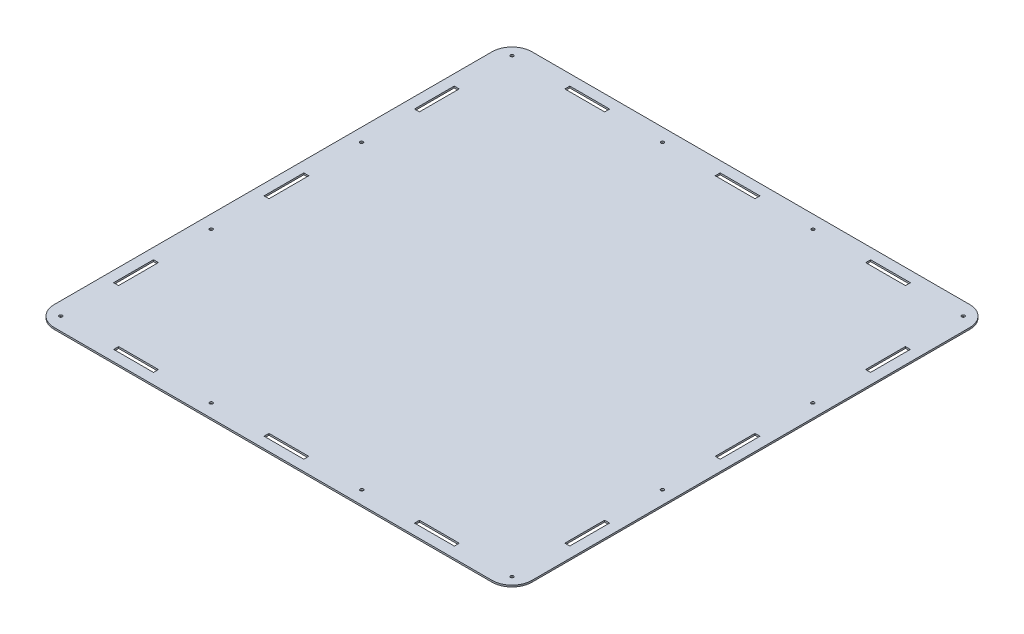
SolidWorks part; units mm, degrees
ref_plane "Front Plane" through (0, 0, 0) normal (0, 0, 1) x (1, 0, 0)
ref_plane "Top Plane" through (0, 0, 0) normal (0, 1, 0) x (1, 0, 0)
ref_plane "Right Plane" through (0, 0, 0) normal (1, 0, 0) x (0, 0, -1)
sketch "Sketch1" plane through (0, 0, 0) normal (0, 1, 0) x (1, 0, 0)
  line L1 (228.6, -228.6) -> (-228.6, -228.6)
  line L2 (228.6, -228.6) -> (228.6, 228.6)
  line L3 (228.6, 228.6) -> (-228.6, 228.6)
  line L4 (-228.6, -228.6) -> (-228.6, 228.6)
  line L5 (228.6, -228.6) -> (-228.6, 228.6) construction
  line L6 (228.6, 228.6) -> (-228.6, -228.6) construction
  point P0 (0, 0)
  dimension "D1" = 457.2
extrude "Boss-Extrude1" add sketch "Sketch1" along normal blind 1.5875
sketch "Sketch2" plane through (0, 1.5875, 0) normal (0, 1, 0) x (1, 0, 0)
  line L0 (-213.5187, -124.8833) -> (-218.2812, -124.8833) construction
  line L1 (-218.2812, -124.8833) -> (-218.2812, -162.9833) construction
  line L2 (-218.2812, -162.9833) -> (-213.5187, -162.9833) construction
  line L3 (-213.5187, -162.9833) -> (-213.5187, -124.8833) construction
  line L4 (-218.2812, -19.05) -> (-213.5187, -19.05) construction
  line L5 (-213.5187, 19.05) -> (-218.2812, 19.05) construction
  line L6 (-218.2812, 19.05) -> (-218.2812, -19.05) construction
  line L7 (-213.5187, -19.05) -> (-213.5187, 19.05) construction
  line L8 (-218.2812, 124.8833) -> (-213.5187, 124.8833) construction
  line L9 (-218.2812, 162.9833) -> (-218.2812, 124.8833) construction
  line L10 (-213.5187, 162.9833) -> (-218.2812, 162.9833) construction
  line L11 (-213.5187, 124.8833) -> (-213.5187, 162.9833) construction
  line L12 (-213.5187, -124.8833) -> (-218.2812, -124.8833)
  line L13 (-218.2812, -124.8833) -> (-218.2812, -162.9833)
  line L14 (-218.2812, -162.9833) -> (-213.5187, -162.9833)
  line L15 (-213.5187, -162.9833) -> (-213.5187, -124.8833)
  line L16 (-218.2812, -19.05) -> (-213.5187, -19.05)
  line L17 (-213.5187, 19.05) -> (-218.2812, 19.05)
  line L18 (-218.2812, 19.05) -> (-218.2812, -19.05)
  line L19 (-213.5187, -19.05) -> (-213.5187, 19.05)
  line L20 (-218.2812, 124.8833) -> (-213.5187, 124.8833)
  line L21 (-218.2812, 162.9833) -> (-218.2812, 124.8833)
  line L22 (-213.5187, 162.9833) -> (-218.2812, 162.9833)
  line L23 (-213.5187, 124.8833) -> (-213.5187, 162.9833)
  line L24 (218.2812, -162.9833) -> (213.5187, -162.9833) construction
  line L25 (213.5187, -124.8833) -> (213.5187, -162.9833) construction
  line L26 (218.2812, -124.8833) -> (218.2812, -162.9833) construction
  line L27 (218.2812, -124.8833) -> (213.5187, -124.8833) construction
  line L28 (218.2812, 19.05) -> (213.5187, 19.05) construction
  line L29 (218.2812, 19.05) -> (218.2812, -19.05) construction
  line L30 (213.5187, 19.05) -> (213.5187, -19.05) construction
  line L31 (218.2812, -19.05) -> (213.5187, -19.05) construction
  line L32 (218.2812, 124.8833) -> (213.5187, 124.8833) construction
  line L33 (218.2812, 162.9833) -> (213.5187, 162.9833) construction
  line L34 (213.5187, 162.9833) -> (213.5187, 124.8833) construction
  line L35 (218.2812, 162.9833) -> (218.2812, 124.8833) construction
  line L36 (218.2812, -162.9833) -> (213.5187, -162.9833)
  line L37 (213.5187, -124.8833) -> (213.5187, -162.9833)
  line L38 (218.2812, -124.8833) -> (218.2812, -162.9833)
  line L39 (218.2812, -124.8833) -> (213.5187, -124.8833)
  line L40 (218.2812, 19.05) -> (213.5187, 19.05)
  line L41 (218.2812, 19.05) -> (218.2812, -19.05)
  line L42 (213.5187, 19.05) -> (213.5187, -19.05)
  line L43 (218.2812, -19.05) -> (213.5187, -19.05)
  line L44 (218.2812, 124.8833) -> (213.5187, 124.8833)
  line L45 (218.2812, 162.9833) -> (213.5187, 162.9833)
  line L46 (213.5187, 162.9833) -> (213.5187, 124.8833)
  line L47 (218.2812, 162.9833) -> (218.2812, 124.8833)
  line L48 (124.968, 218.2813) -> (124.968, 213.5188) construction
  line L49 (163.068, 218.2813) -> (163.068, 213.5188) construction
  line L50 (124.968, 213.5188) -> (163.068, 213.5188) construction
  line L51 (124.968, 218.2813) -> (163.068, 218.2813) construction
  line L52 (-19.05, 218.2813) -> (-19.05, 213.5188) construction
  line L53 (19.05, 218.2813) -> (19.05, 213.5188) construction
  line L54 (-19.05, 213.5188) -> (19.05, 213.5188) construction
  line L55 (-19.05, 218.2813) -> (19.05, 218.2813) construction
  line L56 (-124.841, 218.2813) -> (-124.841, 213.5188) construction
  line L57 (-162.941, 218.2813) -> (-162.941, 213.5188) construction
  line L58 (-162.941, 213.5188) -> (-124.841, 213.5188) construction
  line L59 (-162.941, 218.2813) -> (-124.841, 218.2813) construction
  line L60 (124.968, 218.2813) -> (124.968, 213.5188)
  line L61 (163.068, 218.2813) -> (163.068, 213.5188)
  line L62 (124.968, 213.5188) -> (163.068, 213.5188)
  line L63 (124.968, 218.2813) -> (163.068, 218.2813)
  line L64 (-19.05, 218.2813) -> (-19.05, 213.5188)
  line L65 (19.05, 218.2813) -> (19.05, 213.5188)
  line L66 (-19.05, 213.5188) -> (19.05, 213.5188)
  line L67 (-19.05, 218.2813) -> (19.05, 218.2813)
  line L68 (-124.841, 218.2813) -> (-124.841, 213.5188)
  line L69 (-162.941, 218.2813) -> (-162.941, 213.5188)
  line L70 (-162.941, 213.5188) -> (-124.841, 213.5188)
  line L71 (-162.941, 218.2813) -> (-124.841, 218.2813)
  line L72 (163.068, -218.2812) -> (163.068, -213.5187) construction
  line L73 (124.968, -218.2812) -> (163.068, -218.2812) construction
  line L74 (124.968, -218.2812) -> (124.968, -213.5187) construction
  line L75 (124.968, -213.5187) -> (163.068, -213.5187) construction
  line L76 (-162.941, -218.2812) -> (-162.941, -213.5188) construction
  line L77 (-124.841, -218.2812) -> (-124.841, -213.5188) construction
  line L78 (-162.941, -213.5188) -> (-124.841, -213.5188) construction
  line L79 (-162.941, -218.2812) -> (-124.841, -218.2812) construction
  line L80 (19.05, -218.2812) -> (19.05, -213.5187) construction
  line L81 (-19.05, -218.2812) -> (-19.05, -213.5187) construction
  line L82 (-19.05, -213.5187) -> (19.05, -213.5187) construction
  line L83 (-19.05, -218.2812) -> (19.05, -218.2812) construction
  line L84 (163.068, -218.2812) -> (163.068, -213.5187)
  line L85 (124.968, -218.2812) -> (163.068, -218.2812)
  line L86 (124.968, -218.2812) -> (124.968, -213.5187)
  line L87 (124.968, -213.5187) -> (163.068, -213.5187)
  line L88 (-162.941, -218.2812) -> (-162.941, -213.5188)
  line L89 (-124.841, -218.2812) -> (-124.841, -213.5188)
  line L90 (-162.941, -213.5188) -> (-124.841, -213.5188)
  line L91 (-162.941, -218.2812) -> (-124.841, -218.2812)
  line L92 (19.05, -218.2812) -> (19.05, -213.5187)
  line L93 (-19.05, -218.2812) -> (-19.05, -213.5187)
  line L94 (-19.05, -213.5187) -> (19.05, -213.5187)
  line L95 (-19.05, -218.2812) -> (19.05, -218.2812)
extrude "Cut-Extrude2" cut sketch "Sketch2" against normal up to surface (1.5875 mm away) up to face at (0, 0, 0)
sketch "Sketch3" plane through (0, 1.5875, 0) normal (0, 1, 0) x (1, 0, 0)
  circle A0 centre (-71.882, 215.9) radius 1.4883 construction
  circle A1 centre (72.136, 215.9) radius 1.4883 construction
  circle A2 centre (215.9, 215.9) radius 1.4883 construction
  circle A3 centre (215.9, 71.9667) radius 1.4883 construction
  circle A4 centre (215.9, -71.9667) radius 1.4883 construction
  circle A5 centre (215.9, -215.9) radius 1.4883 construction
  circle A6 centre (72.136, -215.9) radius 1.4883 construction
  circle A7 centre (-71.882, -215.9) radius 1.4883 construction
  circle A8 centre (-215.9, -215.9) radius 1.4883 construction
  circle A9 centre (-215.9, -71.9667) radius 1.4883 construction
  circle A10 centre (-215.9, 71.9667) radius 1.4883 construction
  circle A11 centre (-215.9, 215.9) radius 1.4883 construction
  circle A12 centre (-71.882, 215.9) radius 1.4883
  circle A13 centre (72.136, 215.9) radius 1.4883
  circle A14 centre (215.9, 215.9) radius 1.4883
  circle A15 centre (215.9, 71.9667) radius 1.4883
  circle A16 centre (215.9, -71.9667) radius 1.4883
  circle A17 centre (215.9, -215.9) radius 1.4883
  circle A18 centre (72.136, -215.9) radius 1.4883
  circle A19 centre (-71.882, -215.9) radius 1.4883
  circle A20 centre (-215.9, -215.9) radius 1.4883
  circle A21 centre (-215.9, -71.9667) radius 1.4883
  circle A22 centre (-215.9, 71.9667) radius 1.4883
  circle A23 centre (-215.9, 215.9) radius 1.4883
extrude "Cut-Extrude3" cut sketch "Sketch3" against normal up to surface (1.5875 mm away) up to face at (0, 0, -215.9)
fillet "Fillet1" radius 19.05 4 edges at (228.6, 0.7937, -228.6) (228.6, 0.7937, 228.6) (-228.6, 0.7937, 228.6) (-228.6, 0.7937, -228.6)
equation "\"sheetthickness\"= 3 / 16"
